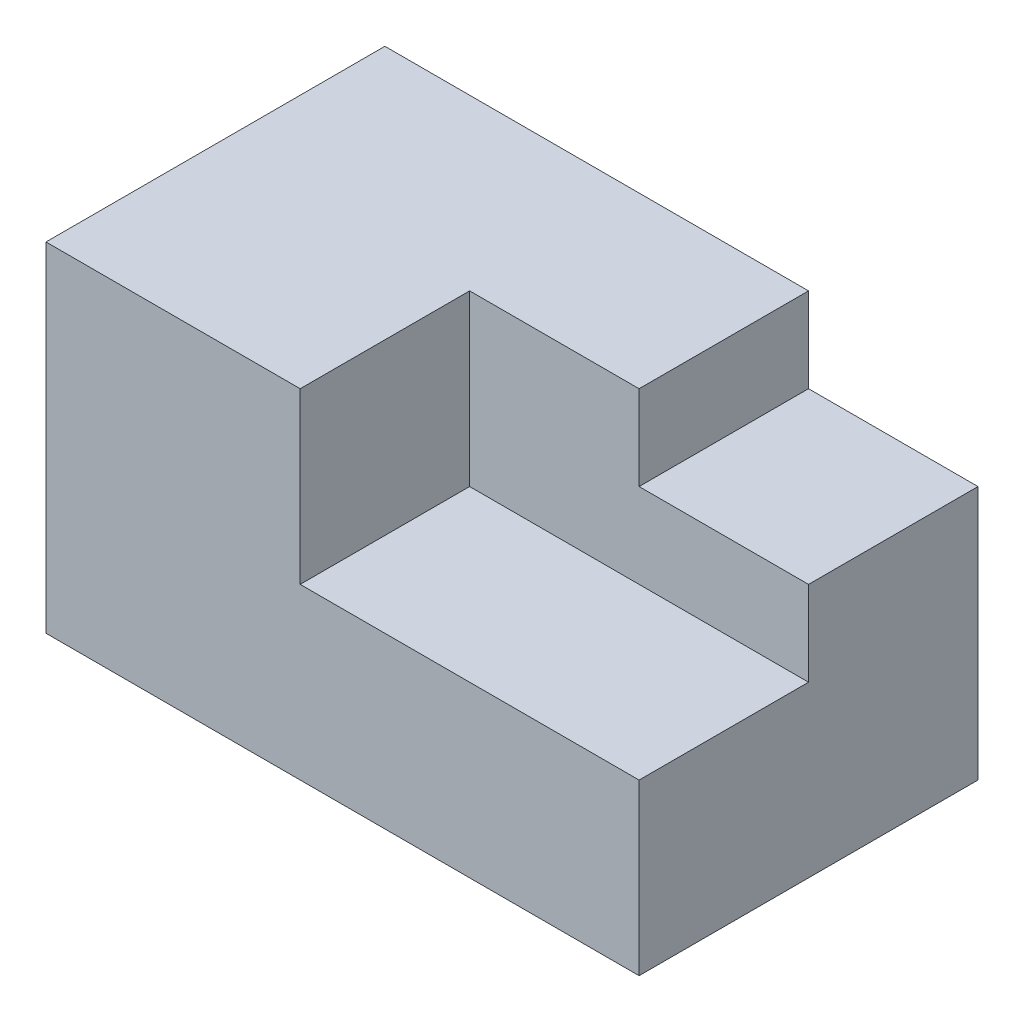
SolidWorks part; units mm, degrees
ref_plane "정면" through (0, 0, 0) normal (0, 0, 1) x (1, 0, 0)
ref_plane "윗면" through (0, 0, 0) normal (0, 1, 0) x (1, 0, 0)
ref_plane "우측면" through (0, 0, 0) normal (1, 0, 0) x (0, 0, -1)
sketch "스케치1" plane through (0, 0, 0) normal (0, 1, 0) x (1, 0, 0)
  line L1 (0, 0) -> (70, 0)
  line L2 (0, 0) -> (0, 40)
  line L3 (0, 40) -> (70, 40)
  line L4 (70, 0) -> (70, 40)
  dimension "D1" = 70
  dimension "D2" = 40
extrude "보스-돌출1" add sketch "스케치1" along normal blind 40
sketch "스케치2" plane through (0, 40, 0) normal (0, 1, 0) x (1, 0, 0)
  line L1 (70, 40) -> (50, 40)
  line L2 (70, 40) -> (70, 20)
  line L3 (70, 20) -> (50, 20)
  line L4 (50, 40) -> (50, 20)
  dimension "D1" = 20
  dimension "D2" = 20
extrude "컷-돌출1" cut sketch "스케치2" against normal blind 10
sketch "스케치3" plane through (0, 40, 0) normal (0, 1, 0) x (1, 0, 0)
  line L1 (70, 0) -> (30, 0)
  line L2 (70, 0) -> (70, 20)
  line L3 (70, 20) -> (30, 20)
  line L4 (30, 0) -> (30, 20)
  dimension "D1" = 20
  dimension "D2" = 40
extrude "컷-돌출2" cut sketch "스케치3" against normal blind 20
